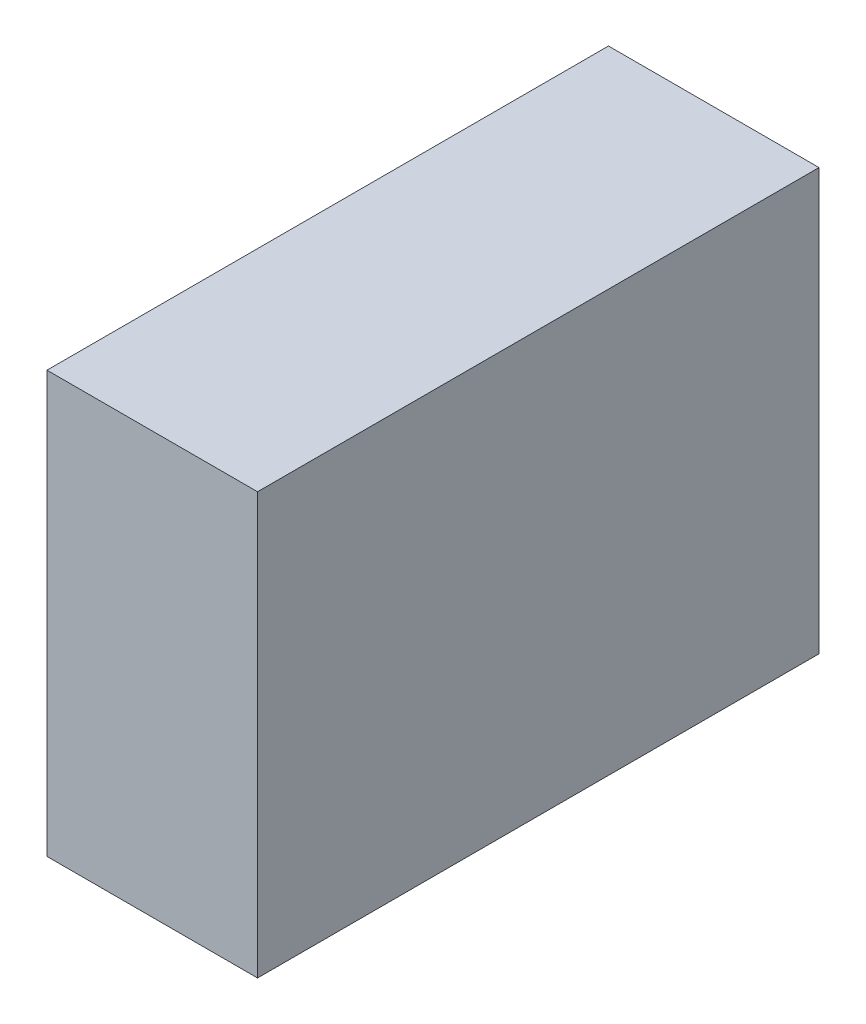
SolidWorks part; units mm, degrees
ref_plane "Front Plane" through (0, 0, 0) normal (0, 0, 1) x (1, 0, 0)
ref_plane "Top Plane" through (0, 0, 0) normal (0, 1, 0) x (1, 0, 0)
ref_plane "Right Plane" through (0, 0, 0) normal (1, 0, 0) x (0, 0, -1)
sketch "Sketch1" plane through (0, 0, 0) normal (0, 0, 1) x (1, 0, 0)
  line L1 (0, 0) -> (57.15, 0)
  line L2 (0, 0) -> (0, 114.3)
  line L3 (0, 114.3) -> (57.15, 114.3)
  line L4 (57.15, 0) -> (57.15, 114.3)
  dimension "D1" = 57.15
  dimension "D2" = 114.3
extrude "Boss-Extrude1" add sketch "Sketch1" along normal blind 152.4
